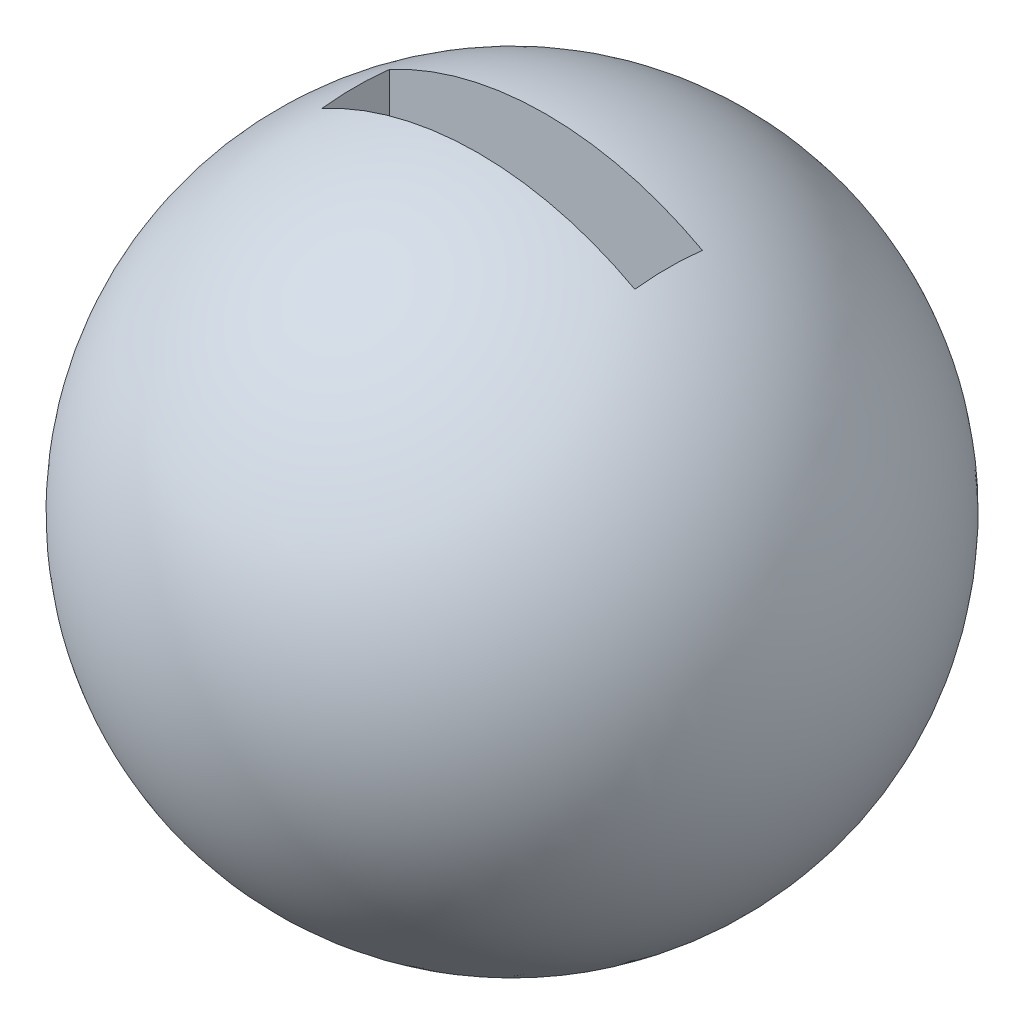
SolidWorks part; units mm, degrees
ref_plane "Front Plane" through (0, 0, 0) normal (0, 0, 1) x (1, 0, 0)
ref_plane "Top Plane" through (0, 0, 0) normal (0, 1, 0) x (1, 0, 0)
ref_plane "Right Plane" through (0, 0, 0) normal (1, 0, 0) x (0, 0, -1)
sketch "Sketch2" plane through (0, 0, 0) normal (0, 1, 0) x (1, 0, 0)
  line L0 (0, 0) -> (0, 50000) construction
  line L1 (0, -10.7355) -> (0, 10.7355)
  arc A0 (0, -10.7355) -> (0, 10.7355) centre (0, 0) ccw
  point P1 (0, 7.4084)
revolve "Revolve1" add sketch "Sketch2" angle 360 about L0
sketch "Sketch5" plane through (0, 0, 0) normal (0, 0, 1) x (1, 0, 0)
  line L1 (-19.8963, -8.6945) -> (19.8963, -8.6945)
  line L2 (-19.8963, -8.6945) -> (-19.8963, -11.4349)
  line L3 (-19.8963, -11.4349) -> (19.8963, -11.4349)
  line L4 (19.8963, -8.6945) -> (19.8963, -11.4349)
  point P4 (0, -8.6945)
  point P6 (0, 0)
extrude "Cut-Extrude2" cut sketch "Sketch5" against normal mid plane 17
sketch "Sketch6" plane through (0, 0, 0) normal (0, 1, 0) x (1, 0, 0)
  line L1 (5.1, -1.1) -> (-5.1, -1.1)
  line L2 (5.1, -1.1) -> (5.1, 1.1)
  line L3 (5.1, 1.1) -> (-5.1, 1.1)
  line L4 (-5.1, -1.1) -> (-5.1, 1.1)
  line L5 (5.1, -1.1) -> (-5.1, 1.1) construction
  line L6 (5.1, 1.1) -> (-5.1, -1.1) construction
  point P0 (0, 0)
  dimension "D1" = 2.2
  dimension "D2" = 10.2
extrude "Cut-Extrude3" cut sketch "Sketch6" along normal up to next
